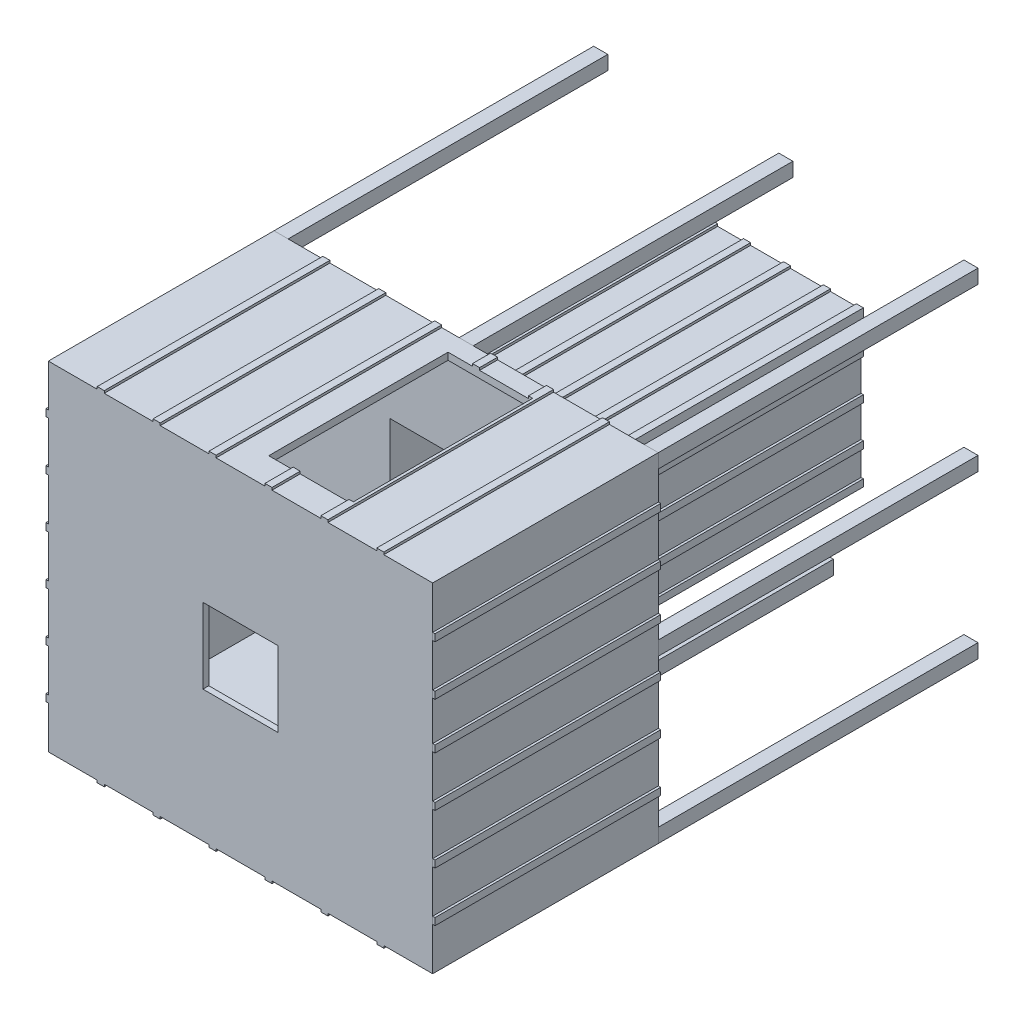
SolidWorks part; units mm, degrees
ref_plane "Front" through (0, 0, 0) normal (0, 0, 1) x (1, 0, 0)
ref_plane "Top" through (0, 0, 0) normal (0, 1, 0) x (1, 0, 0)
ref_plane "Right" through (0, 0, 0) normal (1, 0, 0) x (0, 0, -1)
sketch "Sketch1" plane through (0, 0, 0) normal (0, 0, 1) x (1, 0, 0)
  line L0 (-2076.45, 1828.8) -> (2076.45, -1828.8) construction
  line L1 (-2076.45, 1828.8) -> (2076.45, 1828.8)
  line L2 (-2076.45, 1828.8) -> (-2076.45, -1828.8)
  line L3 (-2076.45, -1828.8) -> (2076.45, -1828.8)
  line L4 (2076.45, 1828.8) -> (2076.45, -1828.8)
  line L5 (-2000.25, 1752.6) -> (-2000.25, -1752.6)
  line L6 (-2000.25, -1752.6) -> (2000.25, -1752.6)
  line L7 (2000.25, 1752.6) -> (2000.25, -1752.6)
  line L8 (-2000.25, 1752.6) -> (2000.25, 1752.6)
  point P4 (0, 0)
  dimension "D1" = 4152.9
  dimension "D2" = 3657.6
  dimension "D3" = 76.2
extrude "Base-Extrude" add sketch "Sketch1" along normal blind 2438.4
sketch "Sketch2" plane through (0, 0, 0) normal (0, 0, -1) x (-1, 0, 0)
  line L0 (-762, -762) -> (762, -762)
  line L1 (-762, 762) -> (-762, -762)
  line L2 (762, 762) -> (-762, 762)
  line L3 (762, -762) -> (762, 762)
  line L4 (2076.45, -1828.8) -> (2076.45, 1828.8)
  line L5 (2076.45, -1828.8) -> (2076.45, 1828.8)
  line L6 (2076.45, 1828.8) -> (-2076.45, 1828.8)
  line L7 (2076.45, 1828.8) -> (-2076.45, 1828.8)
  line L8 (-2076.45, 1828.8) -> (-2076.45, -1828.8)
  line L9 (-2076.45, 1828.8) -> (-2076.45, -1828.8)
  line L10 (-2076.45, -1828.8) -> (2076.45, -1828.8)
  line L11 (-2076.45, -1828.8) -> (2076.45, -1828.8)
  line L12 (-762, 762) -> (762, -762) construction
  dimension "D2" = 1524
  dimension "D3" = 1524
  dimension "D1" = 0
extrude "Boss-Extrude1" add sketch "Sketch2" against normal blind 63.5
sketch "Sketch3" plane through (0, 0, 2438.4) normal (0, 0, 1) x (1, 0, 0)
  line L0 (-406.4, 406.4) -> (406.4, -406.4) construction
  line L1 (-406.4, 406.4) -> (406.4, 406.4)
  line L2 (-406.4, 406.4) -> (-406.4, -406.4)
  line L3 (-406.4, -406.4) -> (406.4, -406.4)
  line L4 (-2076.45, 1828.8) -> (-2076.45, -1828.8)
  line L5 (-2076.45, 1828.8) -> (-2076.45, -1828.8)
  line L6 (-2076.45, -1828.8) -> (2076.45, -1828.8)
  line L7 (-2076.45, -1828.8) -> (2076.45, -1828.8)
  line L8 (2076.45, -1828.8) -> (2076.45, 1828.8)
  line L9 (2076.45, -1828.8) -> (2076.45, 1828.8)
  line L10 (2076.45, 1828.8) -> (-2076.45, 1828.8)
  line L11 (2076.45, 1828.8) -> (-2076.45, 1828.8)
  line L12 (406.4, 406.4) -> (406.4, -406.4)
  circle A1 centre (0, 0) radius 260
  circle A2 centre (0, 0) radius 260 construction
  dimension "D3" = 812.8
  dimension "D4" = 812.8
  dimension "D1" = 0
  dimension "D2" = 0
extrude "Boss-Extrude2" add sketch "Sketch3" against normal blind 63.5
sketch "Sketch4" plane through (0, 0, 0) normal (0, 0, -1) x (-1, 0, 0)
  line L0 (1924.05, 1828.8) -> (2076.45, 1828.8)
  line L1 (-2076.45, 1828.8) -> (2076.45, 1828.8) construction
  line L2 (2076.45, 1828.8) -> (2076.45, 1676.4)
  line L3 (2076.45, 1828.8) -> (2076.45, -1828.8) construction
  line L4 (2076.45, 1676.4) -> (1924.05, 1676.4)
  line L5 (1924.05, 1676.4) -> (1924.05, 1828.8)
  line L6 (0, 1875.0635) -> (0, -1962.1236) construction
  line L7 (-2052.0766, 0) -> (2208.6127, 0) construction
  line L8 (1924.05, -1676.4) -> (1924.05, -1828.8)
  line L9 (1924.05, -1828.8) -> (2076.45, -1828.8)
  line L10 (2076.45, -1828.8) -> (2076.45, -1676.4)
  line L11 (2076.45, -1676.4) -> (1924.05, -1676.4)
  line L12 (-2076.45, -1828.8) -> (-2076.45, -1676.4)
  line L13 (-1924.05, -1828.8) -> (-2076.45, -1828.8)
  line L14 (-1924.05, -1676.4) -> (-1924.05, -1828.8)
  line L15 (-2076.45, -1676.4) -> (-1924.05, -1676.4)
  line L16 (-2076.45, 1676.4) -> (-1924.05, 1676.4)
  line L17 (-1924.05, 1676.4) -> (-1924.05, 1828.8)
  line L18 (-2076.45, 1828.8) -> (-2076.45, 1676.4)
  line L19 (-1924.05, 1828.8) -> (-2076.45, 1828.8)
  line L20 (1928.8125, 1824.0375) -> (2071.6875, 1824.0375)
  line L21 (1928.8125, 1681.1625) -> (1928.8125, 1824.0375)
  line L22 (2071.6875, 1681.1625) -> (1928.8125, 1681.1625)
  line L23 (2071.6875, 1824.0375) -> (2071.6875, 1681.1625)
  line L24 (-2071.6875, 1824.0375) -> (-2071.6875, 1681.1625)
  line L25 (-1928.8125, 1824.0375) -> (-2071.6875, 1824.0375)
  line L26 (-1928.8125, 1681.1625) -> (-1928.8125, 1824.0375)
  line L27 (-2071.6875, 1681.1625) -> (-1928.8125, 1681.1625)
  line L28 (2071.6875, -1824.0375) -> (2071.6875, -1681.1625)
  line L29 (2071.6875, -1681.1625) -> (1928.8125, -1681.1625)
  line L30 (1928.8125, -1681.1625) -> (1928.8125, -1824.0375)
  line L31 (1928.8125, -1824.0375) -> (2071.6875, -1824.0375)
  line L32 (-1928.8125, -1681.1625) -> (-1928.8125, -1824.0375)
  line L33 (-2071.6875, -1681.1625) -> (-1928.8125, -1681.1625)
  line L34 (-2071.6875, -1824.0375) -> (-2071.6875, -1681.1625)
  line L35 (-1928.8125, -1824.0375) -> (-2071.6875, -1824.0375)
  line L36 (781.05, 2100.2481) -> (781.05, -2223.6723) construction
  line L37 (-2317.3549, -457.2) -> (2473.3024, -457.2) construction
  line L38 (709.6125, 1824.0375) -> (852.4875, 1824.0375) construction
  line L39 (704.85, 1828.8) -> (857.25, 1828.8) construction
  line L40 (704.85, 1828.8) -> (704.85, 1676.4) construction
  line L41 (704.85, 1676.4) -> (857.25, 1676.4) construction
  line L42 (857.25, 1828.8) -> (857.25, 1676.4) construction
  line L43 (852.4875, 1824.0375) -> (852.4875, 1681.1625) construction
  line L44 (709.6125, 1681.1625) -> (852.4875, 1681.1625) construction
  line L45 (709.6125, 1824.0375) -> (709.6125, 1681.1625) construction
  line L46 (-2076.45, -1828.8) -> (-2076.45, 1828.8) construction
  line L47 (-2076.45, -381) -> (-1924.05, -381) construction
  line L48 (-2076.45, -381) -> (-2076.45, -533.4) construction
  line L49 (-2076.45, -533.4) -> (-1924.05, -533.4) construction
  line L50 (-1924.05, -381) -> (-1924.05, -533.4) construction
  line L51 (-2071.6875, -385.7625) -> (-1928.8125, -385.7625) construction
  line L52 (-1928.8125, -385.7625) -> (-1928.8125, -528.6375) construction
  line L53 (-2071.6875, -528.6375) -> (-1928.8125, -528.6375) construction
  line L54 (-2071.6875, -385.7625) -> (-2071.6875, -528.6375) construction
  line L55 (2076.45, -1828.8) -> (-2076.45, -1828.8) construction
  line L56 (-76.2, -1828.8) -> (76.2, -1828.8) construction
  line L57 (-76.2, -1828.8) -> (-76.2, -1676.4) construction
  line L58 (-76.2, -1676.4) -> (76.2, -1676.4) construction
  line L59 (76.2, -1828.8) -> (76.2, -1676.4) construction
  line L60 (-71.4375, -1824.0375) -> (71.4375, -1824.0375) construction
  line L61 (71.4375, -1824.0375) -> (71.4375, -1681.1625) construction
  line L62 (-71.4375, -1681.1625) -> (71.4375, -1681.1625) construction
  line L63 (-71.4375, -1824.0375) -> (-71.4375, -1681.1625) construction
  line L64 (2071.6875, -71.4375) -> (1928.8125, -71.4375) construction
  line L65 (2076.45, -76.2) -> (1924.05, -76.2) construction
  line L66 (2076.45, -76.2) -> (2076.45, 76.2) construction
  line L67 (2076.45, 76.2) -> (1924.05, 76.2) construction
  line L68 (1924.05, -76.2) -> (1924.05, 76.2) construction
  line L69 (1928.8125, -71.4375) -> (1928.8125, 71.4375) construction
  line L70 (2071.6875, 71.4375) -> (1928.8125, 71.4375) construction
  line L71 (2071.6875, -71.4375) -> (2071.6875, 71.4375) construction
  line L72 (-71.4375, 1824.0375) -> (-71.4375, 1681.1625)
  line L73 (-71.4375, 1681.1625) -> (71.4375, 1681.1625)
  line L74 (71.4375, 1824.0375) -> (71.4375, 1681.1625)
  line L75 (-71.4375, 1824.0375) -> (71.4375, 1824.0375)
  line L76 (76.2, 1828.8) -> (76.2, 1676.4)
  line L77 (-76.2, 1676.4) -> (76.2, 1676.4)
  line L78 (-76.2, 1828.8) -> (-76.2, 1676.4)
  line L79 (-76.2, 1828.8) -> (76.2, 1828.8)
  line L80 (-3099.1062, -533.4) -> (3294.2058, -533.4) construction
  line L81 (-2076.45, 1676.4) -> (-2076.45, -533.4) construction
  line L82 (-1924.05, 1676.4) -> (-1924.05, -533.4) construction
  line L83 (-1928.8125, -528.6375) -> (-1928.8125, -385.7625) construction
  line L84 (-1924.05, -533.4) -> (-2076.45, -533.4) construction
  line L85 (-1924.05, -533.4) -> (-1924.05, -381) construction
  line L86 (-1924.05, -381) -> (-2076.45, -381) construction
  line L87 (-2076.45, -533.4) -> (-2076.45, -381) construction
  line L88 (-1928.8125, -385.7625) -> (-2071.6875, -385.7625) construction
  line L89 (-2071.6875, -528.6375) -> (-2071.6875, -385.7625) construction
  line L90 (-1928.8125, -528.6375) -> (-2071.6875, -528.6375) construction
  line L91 (-361.95, -2223.6723) -> (-361.95, 2276.0035) construction
  line L92 (-1924.05, -1676.4) -> (1320.7273, -1676.4) construction
  line L93 (-366.7125, -1681.1625) -> (-509.5875, -1681.1625)
  line L94 (-361.95, -1676.4) -> (-514.35, -1676.4)
  line L95 (-361.95, -1676.4) -> (-361.95, -1828.8)
  line L96 (-361.95, -1828.8) -> (-514.35, -1828.8)
  line L97 (-514.35, -1676.4) -> (-514.35, -1828.8)
  line L98 (-509.5875, -1681.1625) -> (-509.5875, -1824.0375)
  line L99 (-366.7125, -1824.0375) -> (-509.5875, -1824.0375)
  line L100 (-366.7125, -1681.1625) -> (-366.7125, -1824.0375)
  line L101 (-2071.6875, -71.4375) -> (-2071.6875, 71.4375)
  line L102 (-2071.6875, 71.4375) -> (-1928.8125, 71.4375)
  line L103 (-1928.8125, -71.4375) -> (-1928.8125, 71.4375)
  line L104 (-1924.05, -76.2) -> (-1924.05, 76.2)
  line L105 (-2076.45, 76.2) -> (-1924.05, 76.2)
  line L106 (-2076.45, -76.2) -> (-2076.45, 76.2)
  line L107 (-2076.45, -76.2) -> (-1924.05, -76.2)
  line L108 (-2071.6875, -71.4375) -> (-1928.8125, -71.4375)
  line L109 (1924.05, -381) -> (2076.45, -381)
  line L110 (1928.8125, -385.7625) -> (2071.6875, -385.7625)
  line L111 (2076.45, -533.4) -> (2076.45, -381)
  line L112 (2071.6875, -528.6375) -> (2071.6875, -385.7625)
  line L113 (1928.8125, -528.6375) -> (2071.6875, -528.6375)
  line L114 (1924.05, -533.4) -> (2076.45, -533.4)
  line L115 (1924.05, -533.4) -> (1924.05, -381)
  line L116 (1928.8125, -528.6375) -> (1928.8125, -385.7625)
  point P50 (781.05, 1828.8)
  point P61 (-2076.45, -457.2)
  point P72 (0, -1828.8)
  point P81 (2076.45, 0)
  dimension "D1" = 152.4
  dimension "D2" = 152.4
  dimension "D4" = 1295.4
  dimension "D5" = 2286
  dimension "D6" = 152.4
  dimension "D7" = 152.4
  dimension "D9" = 152.4
  dimension "D10" = 152.4
  dimension "D12" = 152.4
  dimension "D13" = 152.4
  dimension "D15" = 152.4
  dimension "D16" = 152.4
  dimension "D18" = 1295.4
  dimension "D19" = 152.4
  dimension "D21" = 2438.4
  dimension "D22" = 152.4
  dimension "D3" = 4.7625
  dimension "D8" = 4.7625
  dimension "D11" = 4.7625
  dimension "D14" = 4.7625
  dimension "D17" = 4.7625
  dimension "D20" = 4.7625
  dimension "D23" = 4.7625
extrude "Boss-Extrude3" add sketch "Sketch4" along normal blind 3454.4
sketch "Sketch9" plane through (0, 1828.8, 0) normal (0, 1, 0) x (-1, 0, 0)
  line L0 (1924.05, 0) -> (2076.45, 0)
  line L1 (2076.45, 2438.4) -> (2076.45, -3454.4) construction
  line L2 (-1924.05, 0) -> (-2076.45, 0)
  line L3 (-2076.45, 2438.4) -> (-2076.45, -3454.4) construction
  line L4 (76.2, 0) -> (-76.2, 0)
split line "Split Line4"
sketch "Sketch10" plane through (2076.45, 0, 0) normal (1, 0, 0) x (0, 0, -1)
  line L0 (0, -1676.4) -> (0, -1828.8)
  line L1 (-2438.4, -1828.8) -> (3454.4, -1828.8) construction
  line L2 (0, 76.2) -> (0, -76.2)
  line L3 (0, 1676.4) -> (0, 1828.8)
split line "Split Line5"
sketch "Sketch11" plane through (0, -1828.8, 0) normal (0, -1, 0) x (1, 0, 0)
  line L0 (514.35, 0) -> (361.95, 0)
  line L1 (-1924.05, 0) -> (-2076.45, 0)
  line L2 (-2076.45, 2438.4) -> (-2076.45, -3454.4) construction
  line L3 (1924.05, 0) -> (2076.45, 0)
split line "Split Line6"
sketch "Sketch12" plane through (-2076.45, 0, 0) normal (-1, 0, 0) x (0, 0, 1)
  line L0 (0, 1828.8) -> (0, 1676.4)
  line L1 (0, -381) -> (0, -533.4)
  line L2 (0, -1676.4) -> (0, -1828.8)
split line "Split Line7"
sketch "Sketch13" plane through (0, 1828.8, 0) normal (0, 1, 0) x (1, 0, 0)
  line L0 (1924.05, 0) -> (76.2, 0) construction
  line L1 (1548.4929, 0) -> (1472.2929, 0)
  line L2 (1548.4929, 0) -> (1548.4929, -2438.4)
  line L3 (1548.4929, -2438.4) -> (1472.2929, -2438.4)
  line L4 (1472.2929, 0) -> (1472.2929, -2438.4)
  line L5 (2076.45, -2438.4) -> (-2076.45, -2438.4) construction
  line L6 (-76.2, 0) -> (-1924.05, 0) construction
  line L7 (944.3357, 0) -> (868.1357, 0)
  line L8 (944.3357, 0) -> (944.3357, -2438.4)
  line L9 (944.3357, -2438.4) -> (868.1357, -2438.4)
  line L10 (868.1357, 0) -> (868.1357, -2438.4)
  line L11 (340.1786, 0) -> (263.9786, 0)
  line L12 (340.1786, 0) -> (340.1786, -2438.4)
  line L13 (340.1786, -2438.4) -> (263.9786, -2438.4)
  line L14 (263.9786, 0) -> (263.9786, -2438.4)
  line L15 (-263.9786, 0) -> (-340.1786, 0)
  line L16 (-263.9786, 0) -> (-263.9786, -2438.4)
  line L17 (-263.9786, -2438.4) -> (-340.1786, -2438.4)
  line L18 (-340.1786, 0) -> (-340.1786, -2438.4)
  line L19 (-868.1357, 0) -> (-944.3357, 0)
  line L20 (-868.1357, 0) -> (-868.1357, -2438.4)
  line L21 (-868.1357, -2438.4) -> (-944.3357, -2438.4)
  line L22 (-944.3357, 0) -> (-944.3357, -2438.4)
  line L23 (1548.4929, -2438.4) -> (2076.45, -2438.4)
  line L24 (-1472.2929, 0) -> (-1548.4929, 0)
  line L25 (-1472.2929, 0) -> (-1472.2929, -2438.4)
  line L26 (-1472.2929, -2438.4) -> (-1548.4929, -2438.4)
  line L27 (-1548.4929, 0) -> (-1548.4929, -2438.4)
  line L28 (-2076.45, -2438.4) -> (-2076.45, 0) construction
  line L32 (-2076.45, -2438.4) -> (-1548.4929, -2438.4)
  line L33 (-1472.2929, -2438.4) -> (-944.3357, -2438.4)
  line L34 (-868.1357, -2438.4) -> (-340.1786, -2438.4)
  line L35 (-263.9786, -2438.4) -> (263.9786, -2438.4)
  line L36 (263.9786, -2438.4) -> (254.571, -2429.2212)
  line L37 (340.1786, -2438.4) -> (868.1357, -2438.4)
  line L38 (944.3357, -2438.4) -> (1472.2929, -2438.4)
  line L39 (1548.4929, -2438.4) -> (2076.45, -2438.4)
  line M2 (-76.2, 0) -> (-1924.05, 0)
  line M5 (-2076.45, -2438.4) -> (2076.45, -2438.4)
  line M8 (1924.05, 0) -> (76.2, 0)
  dimension "D1" = 76.2
  dimension "D2" = 76.2
  dimension "D3" = 76.2
  dimension "D4" = 76.2
  dimension "D5" = 76.2
  dimension "D6" = 76.2
extrude "Boss-Extrude5" add sketch "Sketch13" along normal blind 25.4 contours L27 L25 M2 M5 | L22 L20 M2 M5 | L18 L16 M2 M5 | L14 L12 M8 M5 | L10 L8 M8 M5 | L4 L2 M8 M5
sketch "Sketch15" plane through (0, -1828.8, 0) normal (0, -1, 0) x (1, 0, 0)
  line L0 (1548.4929, 2438.4) -> (1472.2929, 2438.4)
  line L1 (1548.4929, 2438.4) -> (1548.4929, 0)
  line L2 (1548.4929, 0) -> (1472.2929, 0)
  line L3 (1472.2929, 2438.4) -> (1472.2929, 0)
  line L4 (944.3357, 2438.4) -> (868.1357, 2438.4)
  line L5 (944.3357, 2438.4) -> (944.3357, 0)
  line L6 (944.3357, 0) -> (868.1357, 0)
  line L7 (868.1357, 2438.4) -> (868.1357, 0)
  line L8 (340.1786, 2438.4) -> (263.9786, 2438.4)
  line L9 (340.1786, 2438.4) -> (340.1786, 0)
  line L10 (340.1786, 0) -> (263.9786, 0)
  line L11 (263.9786, 2438.4) -> (263.9786, 0)
  line L12 (-263.9786, 2438.4) -> (-340.1786, 2438.4)
  line L13 (-263.9786, 2438.4) -> (-263.9786, 0)
  line L14 (-263.9786, 0) -> (-340.1786, 0)
  line L15 (-340.1786, 2438.4) -> (-340.1786, 0)
  line L16 (-868.1357, 2438.4) -> (-944.3357, 2438.4)
  line L17 (-868.1357, 2438.4) -> (-868.1357, 0)
  line L18 (-868.1357, 0) -> (-944.3357, 0)
  line L19 (-944.3357, 2438.4) -> (-944.3357, 0)
  line L20 (1548.4929, 0) -> (2076.45, 0)
  line L21 (-1472.2929, 2438.4) -> (-1548.4929, 2438.4)
  line L22 (-1472.2929, 2438.4) -> (-1472.2929, 0)
  line L23 (-1472.2929, 0) -> (-1548.4929, 0)
  line L24 (-1548.4929, 2438.4) -> (-1548.4929, 0)
  line L25 (-2076.45, 0) -> (-1548.4929, 0)
  line L26 (-1472.2929, 0) -> (-944.3357, 0)
  line L27 (-868.1357, 0) -> (-340.1786, 0)
  line L28 (-263.9786, 0) -> (263.9786, 0)
  line L29 (-2076.45, 2438.4) -> (2076.45, 2438.4) construction
  line L30 (340.1786, 0) -> (868.1357, 0)
  line L31 (944.3357, 0) -> (1472.2929, 0)
  line L32 (1548.4929, 0) -> (2076.45, 0)
  line L33 (-2076.45, 2438.4) -> (-2076.45, 0) construction
  line M1 (514.35, 0) -> (1924.05, 0)
  line M4 (2076.45, 2438.4) -> (-2076.45, 2438.4)
  line M7 (-1924.05, 0) -> (361.95, 0)
  dimension "D1" = 76.2
  dimension "D2" = 76.2
  dimension "D3" = 76.2
  dimension "D4" = 76.2
  dimension "D5" = 76.2
  dimension "D6" = 76.2
extrude "Boss-Extrude6" add sketch "Sketch15" along normal blind 25.4 contours L24 L22 M4 M7 | L19 L17 M4 M7 | L15 L13 M4 M7 | L11 L9 M4 M7 | L7 L5 M4 M1 | L3 L1 M4 M1
sketch "Sketch16" plane through (2076.45, 0, 0) normal (1, 0, 0) x (0, 0, -1)
  line L0 (0, -1676.4) -> (0, -76.2) construction
  line L1 (0, -1366.3407) -> (-2438.4, -1366.3407)
  line L2 (0, -1366.3407) -> (0, -1290.1407)
  line L3 (0, -1290.1407) -> (-2438.4, -1290.1407)
  line L4 (-2438.4, -1366.3407) -> (-2438.4, -1290.1407)
  line L5 (-2438.4, -1828.8) -> (-2438.4, 1828.8) construction
  line L6 (0, -827.6815) -> (-2438.4, -827.6815)
  line L7 (0, -827.6815) -> (0, -751.4815)
  line L8 (0, -751.4815) -> (-2438.4, -751.4815)
  line L9 (-2438.4, -827.6815) -> (-2438.4, -751.4815)
  line L10 (0, -289.0222) -> (-2438.4, -289.0222)
  line L11 (0, -289.0222) -> (0, -212.8222)
  line L12 (0, -212.8222) -> (-2438.4, -212.8222)
  line L13 (-2438.4, -289.0222) -> (-2438.4, -212.8222)
  line L14 (0, 249.637) -> (-2438.4, 249.637)
  line L15 (0, 249.637) -> (0, 325.837)
  line L16 (0, 325.837) -> (-2438.4, 325.837)
  line L17 (-2438.4, 249.637) -> (-2438.4, 325.837)
  line L18 (0, 751.4815) -> (-2438.4, 751.4815)
  line L19 (0, 751.4815) -> (0, 827.6815)
  line L20 (0, 827.6815) -> (-2438.4, 827.6815)
  line L21 (-2438.4, 751.4815) -> (-2438.4, 827.6815)
  line L22 (0, 1290.1407) -> (-2438.4, 1290.1407)
  line L23 (0, 1290.1407) -> (0, 1366.3407)
  line L24 (0, 1366.3407) -> (-2438.4, 1366.3407)
  line L25 (-2438.4, 1290.1407) -> (-2438.4, 1366.3407)
  line L26 (0, 76.2) -> (0, 1676.4) construction
  line L27 (0, -1828.8) -> (0, -1366.3407)
  line L28 (0, -1290.1407) -> (0, -827.6815)
  line L29 (0, -751.4815) -> (0, -289.0222)
  line L30 (0, -212.8222) -> (0, 249.637)
  line L31 (0, 325.837) -> (0, 751.4815)
  line L32 (0, 827.6815) -> (0, 1290.1407)
  line L33 (0, 1366.3407) -> (0, 1828.8)
  line M1 (0, 76.2) -> (0, 1676.4)
  line M4 (-2438.4, 1828.8) -> (-2438.4, -1828.8)
  line M7 (0, -1676.4) -> (0, -76.2)
  dimension "D1" = 76.2
  dimension "D2" = 76.2
  dimension "D3" = 76.2
  dimension "D4" = 76.2
  dimension "D5" = 76.2
  dimension "D6" = 76.2
extrude "Boss-Extrude7" add sketch "Sketch16" along normal blind 25.4 separate body contours L3 L1 M7 M4 | L8 L6 M7 M4 | L12 L10 M7 M4 | L16 L14 M1 M4 | L20 L18 M1 M4 | L24 L22 M1 M4
sketch "Sketch19" plane through (-2076.45, 0, 0) normal (-1, 0, 0) x (0, 0, 1)
  line L0 (2438.4, -1371.6) -> (0, -1371.6)
  line L1 (2438.4, -1371.6) -> (2438.4, -1295.4)
  line L2 (2438.4, -1295.4) -> (0, -1295.4)
  line L3 (0, -1371.6) -> (0, -1295.4)
  line L4 (2438.4, -838.2) -> (0, -838.2)
  line L5 (2438.4, -838.2) -> (2438.4, -762)
  line L6 (2438.4, -762) -> (0, -762)
  line L7 (0, -838.2) -> (0, -762)
  line L8 (2438.4, -304.8) -> (0, -304.8)
  line L9 (2438.4, -304.8) -> (2438.4, -228.6)
  line L10 (2438.4, -228.6) -> (0, -228.6)
  line L11 (0, -304.8) -> (0, -228.6)
  line L12 (2438.4, 228.6) -> (0, 228.6)
  line L13 (2438.4, 228.6) -> (2438.4, 304.8)
  line L14 (2438.4, 304.8) -> (0, 304.8)
  line L15 (0, 228.6) -> (0, 304.8)
  line L16 (2438.4, 762) -> (0, 762)
  line L17 (2438.4, 762) -> (2438.4, 838.2)
  line L18 (2438.4, 838.2) -> (0, 838.2)
  line L19 (0, 762) -> (0, 838.2)
  line L20 (2438.4, 1295.4) -> (0, 1295.4)
  line L21 (2438.4, 1295.4) -> (2438.4, 1371.6)
  line L22 (2438.4, 1371.6) -> (0, 1371.6)
  line L23 (0, 1295.4) -> (0, 1371.6)
  line L24 (2438.4, -1828.8) -> (2438.4, -1371.6)
  line L25 (2438.4, -1295.4) -> (2438.4, -838.2)
  line L26 (2438.4, -762) -> (2438.4, -304.8)
  line L27 (2438.4, -228.6) -> (2438.4, 228.6)
  line L28 (2438.4, 304.8) -> (2438.4, 762)
  line L29 (2438.4, 838.2) -> (2438.4, 1295.4)
  line L30 (2438.4, 1371.6) -> (2438.4, 1828.8)
  line L31 (0, 1676.4) -> (0, -381) construction
  line L32 (0, -533.4) -> (0, -1676.4) construction
  line M1 (0, -533.4) -> (0, -1676.4)
  line M4 (2438.4, -1828.8) -> (2438.4, 1828.8)
  line M7 (0, 1676.4) -> (0, -381)
  dimension "D1" = 76.2
  dimension "D2" = 76.2
  dimension "D3" = 76.2
  dimension "D4" = 76.2
  dimension "D5" = 76.2
  dimension "D6" = 76.2
extrude "Boss-Extrude8" add sketch "Sketch19" along normal blind 25.4 contours L22 L20 M4 M7 | L18 L16 M4 M7 | L14 L12 M4 M7 | L10 L8 M4 M7 | L6 L4 M4 M1 | L2 L0 M4 M1
sketch "Sketch22" plane through (0, 0, 0) normal (0, 0, -1) x (-1, 0, 0)
  line L1 (-762, 762) -> (762, 762)
  line L2 (-762, 762) -> (-762, -762)
  line L3 (-762, -762) -> (762, -762)
  line L4 (762, 762) -> (762, -762)
  line L5 (-762, 762) -> (762, -762) construction
  line L6 (-762, -762) -> (762, 762) construction
  line L7 (-812.8, 812.8) -> (812.8, 812.8)
  line L8 (-812.8, 812.8) -> (-812.8, -812.8)
  line L9 (-812.8, -812.8) -> (812.8, -812.8)
  line L10 (812.8, 812.8) -> (812.8, -812.8)
  line L11 (-812.8, 812.8) -> (812.8, -812.8) construction
  line L12 (-812.8, -812.8) -> (812.8, 812.8) construction
  point P0 (0, 0)
  point P7 (0, 0)
  dimension "D1" = 50.8
extrude "Boss-Extrude9" add sketch "Sketch22" along normal up to vertex (3454.4 mm away)
sketch "Sketch24" plane through (0, -812.8, 0) normal (0, -1, 0) x (1, 0, 0)
  line L0 (812.8, -3454.4) -> (-812.8, -3454.4) construction
  line L1 (-463.55, -3454.4) -> (-387.35, -3454.4)
  line L2 (-463.55, -3454.4) -> (-463.55, 0)
  line L3 (-463.55, 0) -> (-387.35, 0)
  line L4 (-387.35, -3454.4) -> (-387.35, 0)
  line L5 (812.8, 0) -> (-812.8, 0) construction
  line L6 (-38.1, -3454.4) -> (38.1, -3454.4)
  line L7 (-38.1, -3454.4) -> (-38.1, 0)
  line L8 (-38.1, 0) -> (38.1, 0)
  line L9 (38.1, -3454.4) -> (38.1, 0)
  line L10 (387.35, -3454.4) -> (463.55, -3454.4)
  line L11 (387.35, -3454.4) -> (387.35, 0)
  line L12 (387.35, 0) -> (463.55, 0)
  line L13 (463.55, -3454.4) -> (463.55, 0)
  line L15 (-812.8, -3454.4) -> (-463.55, -3454.4)
  line L16 (-387.35, -3454.4) -> (-38.1, -3454.4)
  line L17 (38.1, -3454.4) -> (387.35, -3454.4)
  line L18 (463.55, -3454.4) -> (812.8, -3454.4)
  line L19 (-812.8, -3454.4) -> (-736.6, -3454.4)
  line L20 (-812.8, -3454.4) -> (-812.8, 0)
  line L21 (-812.8, 0) -> (-736.6, 0)
  line L22 (-736.6, -3454.4) -> (-736.6, 0)
  line L23 (812.8, 0) -> (736.6, 0)
  line L24 (812.8, 0) -> (812.8, -3454.4)
  line L25 (812.8, -3454.4) -> (736.6, -3454.4)
  line L26 (736.6, 0) -> (736.6, -3454.4)
  line M1 (812.8, 0) -> (-812.8, 0)
  line M2 (-812.8, 0) -> (-812.8, -3454.4)
  line M3 (-812.8, -3454.4) -> (812.8, -3454.4)
  line M4 (812.8, -3454.4) -> (812.8, 0)
  dimension "D1" = 76.2
  dimension "D2" = 76.2
  dimension "D3" = 76.2
  dimension "D4" = 76.2
  dimension "D5" = 76.2
extrude "Boss-Extrude10" add sketch "Sketch24" along normal blind 25.4 contours L22 M3 M1 M2 | L4 L2 M3 M1 | L9 L7 M3 M1 | L13 L11 M3 M1 | L26 L18 M1 M4
sketch "Sketch27" plane through (812.8, 0, 0) normal (1, 0, 0) x (0, 0, -1)
  line L0 (3454.4, 812.8) -> (3454.4, -838.2) construction
  line L1 (3454.4, -482.6) -> (0, -482.6)
  line L2 (3454.4, -482.6) -> (3454.4, -406.4)
  line L3 (3454.4, -406.4) -> (0, -406.4)
  line L4 (0, -482.6) -> (0, -406.4)
  line L5 (0, 812.8) -> (0, -838.2) construction
  line L6 (3454.4, -838.2) -> (3454.4, -482.6)
  line L7 (0, -50.8) -> (3454.4, -50.8)
  line L8 (0, -50.8) -> (0, 25.4)
  line L9 (0, 25.4) -> (3454.4, 25.4)
  line L10 (3454.4, -50.8) -> (3454.4, 25.4)
  line L11 (0, 381) -> (3454.4, 381)
  line L12 (0, 381) -> (0, 457.2)
  line L13 (0, 457.2) -> (3454.4, 457.2)
  line L14 (3454.4, 381) -> (3454.4, 457.2)
  line L15 (3454.4, -406.4) -> (3454.4, -50.8)
  line L16 (3454.4, 25.4) -> (3454.4, 381)
  line L17 (3454.4, 457.2) -> (3454.4, 812.8)
  line L19 (3454.4, -838.2) -> (0, -838.2)
  line L20 (3454.4, -838.2) -> (3454.4, -762)
  line L21 (3454.4, -762) -> (0, -762)
  line L22 (0, -838.2) -> (0, -762)
  line L23 (3454.4, 812.8) -> (0, 812.8)
  line L24 (3454.4, 812.8) -> (3454.4, 736.6)
  line L25 (3454.4, 736.6) -> (0, 736.6)
  line L26 (0, 812.8) -> (0, 736.6)
  line M1 (0, 812.8) -> (0, -838.2)
  line M2 (0, -838.2) -> (3454.4, -838.2)
  line M3 (3454.4, -838.2) -> (3454.4, 812.8)
  line M4 (3454.4, 812.8) -> (0, 812.8)
  dimension "D1" = 76.2
  dimension "D2" = 76.2
  dimension "D3" = 76.2
  dimension "D4" = 76.2
  dimension "D5" = 76.2
extrude "Boss-Extrude11" add sketch "Sketch27" along normal blind 25.4 contours L21 M3 M1 M2 | L3 L1 M3 M1 | L9 L7 M1 M3 | L13 L11 M1 M3 | L25 L17 M4 M1
sketch "Sketch28" plane through (0, 812.8, 0) normal (0, 1, 0) x (1, 0, 0)
  line L0 (-812.8, 3454.4) -> (838.2, 3454.4) construction
  line L1 (482.6, 3454.4) -> (406.4, 3454.4)
  line L2 (482.6, 3454.4) -> (482.6, 0)
  line L3 (482.6, 0) -> (406.4, 0)
  line L4 (406.4, 3454.4) -> (406.4, 0)
  line L5 (-812.8, 0) -> (838.2, 0) construction
  line L6 (482.6, 3454.4) -> (838.2, 3454.4)
  line L7 (50.8, 0) -> (-25.4, 0)
  line L8 (50.8, 0) -> (50.8, 3454.4)
  line L9 (50.8, 3454.4) -> (-25.4, 3454.4)
  line L10 (-25.4, 0) -> (-25.4, 3454.4)
  line L11 (-381, 3454.4) -> (-457.2, 3454.4)
  line L12 (-381, 3454.4) -> (-381, 0)
  line L13 (-381, 0) -> (-457.2, 0)
  line L14 (-457.2, 3454.4) -> (-457.2, 0)
  line L15 (406.4, 3454.4) -> (50.8, 3454.4)
  line L16 (-25.4, 3454.4) -> (-381, 3454.4)
  line L17 (-457.2, 3454.4) -> (-812.8, 3454.4)
  line L19 (838.2, 3454.4) -> (762, 3454.4)
  line L20 (838.2, 3454.4) -> (838.2, 0)
  line L21 (838.2, 0) -> (762, 0)
  line L22 (762, 3454.4) -> (762, 0)
  line L23 (-812.8, 0) -> (-736.6, 0)
  line L24 (-812.8, 0) -> (-812.8, 3454.4)
  line L25 (-812.8, 3454.4) -> (-736.6, 3454.4)
  line L26 (-736.6, 0) -> (-736.6, 3454.4)
  line M1 (-812.8, 0) -> (838.2, 0)
  line M2 (838.2, 0) -> (838.2, 3454.4)
  line M3 (838.2, 3454.4) -> (-812.8, 3454.4)
  line M4 (-812.8, 3454.4) -> (-812.8, 0)
  dimension "D1" = 76.2
  dimension "D2" = 76.2
  dimension "D3" = 76.2
  dimension "D4" = 76.2
  dimension "D5" = 76.2
extrude "Boss-Extrude12" add sketch "Sketch28" along normal blind 25.4 contours L22 M3 M1 M2 | L4 L2 M3 M1 | L10 L8 M1 M3 | L14 L12 M3 M1 | L26 L17 M1 M4
sketch "Sketch29" plane through (-812.8, 0, 0) normal (-1, 0, 0) x (0, 0, 1)
  line L0 (0, -838.2) -> (0, 838.2) construction
  line L1 (0, 476.25) -> (-3454.4, 476.25)
  line L2 (0, 476.25) -> (0, 400.05)
  line L3 (0, 400.05) -> (-3454.4, 400.05)
  line L4 (-3454.4, 476.25) -> (-3454.4, 400.05)
  line L5 (-3454.4, -838.2) -> (-3454.4, 838.2) construction
  line L6 (-3454.4, 838.2) -> (-3454.4, 476.25)
  line L7 (0, 38.1) -> (-3454.4, 38.1)
  line L8 (0, 38.1) -> (0, -38.1)
  line L9 (0, -38.1) -> (-3454.4, -38.1)
  line L10 (-3454.4, 38.1) -> (-3454.4, -38.1)
  line L11 (0, -400.05) -> (-3454.4, -400.05)
  line L12 (0, -400.05) -> (0, -476.25)
  line L13 (0, -476.25) -> (-3454.4, -476.25)
  line L14 (-3454.4, -400.05) -> (-3454.4, -476.25)
  line L15 (-3454.4, 400.05) -> (-3454.4, 38.1)
  line L16 (-3454.4, -38.1) -> (-3454.4, -400.05)
  line L17 (-3454.4, -476.25) -> (-3454.4, -838.2)
  line L19 (0, 838.2) -> (-3454.4, 838.2)
  line L20 (0, 838.2) -> (0, 762)
  line L21 (0, 762) -> (-3454.4, 762)
  line L22 (-3454.4, 838.2) -> (-3454.4, 762)
  line L23 (-3454.4, -838.2) -> (0, -838.2)
  line L24 (-3454.4, -838.2) -> (-3454.4, -762)
  line L25 (-3454.4, -762) -> (0, -762)
  line L26 (0, -838.2) -> (0, -762)
  line M1 (0, -838.2) -> (0, 838.2)
  line M2 (0, 838.2) -> (-3454.4, 838.2)
  line M3 (-3454.4, 838.2) -> (-3454.4, -838.2)
  line M4 (-3454.4, -838.2) -> (0, -838.2)
  dimension "D1" = 76.2
  dimension "D2" = 76.2
  dimension "D3" = 76.2
  dimension "D4" = 76.2
  dimension "D5" = 76.2
extrude "Boss-Extrude13" add sketch "Sketch29" along normal blind 25.4 contours L21 M1 M2 M3 | L3 L1 M1 M3 | L9 L7 M1 M3 | L13 L11 M1 M3 | L25 L17 M4 M1
sketch "Sketch31" plane through (-812.8, 0, 0) normal (-1, 0, 0) x (0, 0, 1)
  line L0 (-3454.4, 38.1) -> (-3454.4, 400.05) construction
  line L1 (-3454.4, 497.2184) -> (-1473.2, 497.2184)
  line L2 (-3454.4, 497.2184) -> (-3454.4, -493.3816)
  line L3 (-3454.4, -493.3816) -> (-1473.2, -493.3816)
  line L4 (-1473.2, 497.2184) -> (-1473.2, -493.3816)
  line L5 (-3454.4, 476.25) -> (-3454.4, 762) construction
  dimension "D1" = 990.6
  dimension "D2" = 1981.2
extrude "Cut-Extrude5" cut sketch "Sketch31" against normal blind 320.04 and the other way blind 293.37
sketch "Sketch33" plane through (0, 1828.8, 0) normal (0, 1, 0) x (1, 0, 0)
  line L7 (868.1357, 0) -> (340.1786, 0) construction
  line L8 (914.4, 0) -> (-914.4, 0)
  line L9 (914.4, 0) -> (914.4, -2133.6)
  line L10 (914.4, -2133.6) -> (-914.4, -2133.6)
  line L11 (-914.4, 0) -> (-914.4, -2133.6)
  line L12 (914.4, 0) -> (2076.45, 0)
  line L13 (-914.4, 0) -> (-2076.45, 0)
  line L14 (914.4, -76.2) -> (-914.4, -76.2)
  line M1 (263.9786, -2438.4) -> (263.9786, 0)
  line M5 (-263.9786, 0) -> (-263.9786, -2438.4)
  dimension "D4" = 1828.8
  dimension "D5" = 2133.6
  dimension "D6" = 76.2
extrude "Cut-Extrude6" cut sketch "Sketch33" against normal blind 655.574 and the other way blind 320.04 contours L9 L14 L10 M1 | L14 L10 M1 M5 | L14 L11 L10 M5
sketch "Sketch34" plane through (0, 0, 76.2) normal (0, 0, 1) x (1, 0, 0)
  line L16 (914.4, 1752.6) -> (914.4, 1854.2)
  line L17 (914.4, 1854.2) -> (868.1357, 1854.2)
  line L18 (868.1357, 1854.2) -> (868.1357, 1828.8)
  line L19 (868.1357, 1828.8) -> (340.1786, 1828.8)
  line L20 (340.1786, 1828.8) -> (340.1786, 1854.2)
  line L21 (340.1786, 1854.2) -> (263.9786, 1854.2)
  line L22 (263.9786, 1854.2) -> (263.9786, 1828.8)
  line L23 (263.9786, 1828.8) -> (-263.9786, 1828.8)
  line L24 (-263.9786, 1828.8) -> (-263.9786, 1854.2)
  line L25 (-263.9786, 1854.2) -> (-340.1786, 1854.2)
  line L26 (-340.1786, 1854.2) -> (-340.1786, 1828.8)
  line L27 (-340.1786, 1828.8) -> (-868.1357, 1828.8)
  line L28 (-868.1357, 1828.8) -> (-868.1357, 1854.2)
  line L29 (-868.1357, 1854.2) -> (-914.4, 1854.2)
  line L30 (-914.4, 1854.2) -> (-914.4, 1752.6)
  line L31 (-914.4, 1752.6) -> (914.4, 1752.6)
  line L32 (914.4, 1752.6) -> (914.4, 1854.2)
  line L33 (914.4, 1854.2) -> (868.1357, 1854.2)
  line L34 (868.1357, 1854.2) -> (868.1357, 1828.8)
  line L35 (868.1357, 1828.8) -> (340.1786, 1828.8)
  line L36 (340.1786, 1828.8) -> (340.1786, 1854.2)
  line L37 (340.1786, 1854.2) -> (263.9786, 1854.2)
  line L38 (263.9786, 1854.2) -> (263.9786, 1828.8)
  line L39 (263.9786, 1828.8) -> (-263.9786, 1828.8)
  line L40 (-263.9786, 1828.8) -> (-263.9786, 1854.2)
  line L41 (-263.9786, 1854.2) -> (-340.1786, 1854.2)
  line L42 (-340.1786, 1854.2) -> (-340.1786, 1828.8)
  line L43 (-340.1786, 1828.8) -> (-868.1357, 1828.8)
  line L44 (-868.1357, 1828.8) -> (-868.1357, 1854.2)
  line L45 (-868.1357, 1854.2) -> (-914.4, 1854.2)
  line L46 (-914.4, 1854.2) -> (-914.4, 1752.6)
  line L47 (-914.4, 1752.6) -> (914.4, 1752.6)
  dimension "D1" = 0
extrude "Boss-Extrude15" add sketch "Sketch34" along normal blind 119.38
sketch "Sketch35" plane through (0, 0, 195.58) normal (0, 0, 1) x (1, 0, 0)
  line L0 (0, 1828.8) -> (0, 1752.6)
  line L16 (-914.4, 1752.6) -> (914.4, 1752.6)
  line L17 (914.4, 1752.6) -> (914.4, 1854.2)
  line L18 (914.4, 1854.2) -> (868.1357, 1854.2)
  line L19 (868.1357, 1854.2) -> (868.1357, 1828.8)
  line L20 (868.1357, 1828.8) -> (340.1786, 1828.8)
  line L21 (340.1786, 1828.8) -> (340.1786, 1854.2)
  line L22 (340.1786, 1854.2) -> (263.9786, 1854.2)
  line L23 (263.9786, 1854.2) -> (263.9786, 1828.8)
  line L24 (263.9786, 1828.8) -> (-263.9786, 1828.8)
  line L25 (-263.9786, 1828.8) -> (-263.9786, 1854.2)
  line L26 (-263.9786, 1854.2) -> (-340.1786, 1854.2)
  line L27 (-340.1786, 1854.2) -> (-340.1786, 1828.8)
  line L28 (-340.1786, 1828.8) -> (-868.1357, 1828.8)
  line L29 (-868.1357, 1828.8) -> (-868.1357, 1854.2)
  line L30 (-868.1357, 1854.2) -> (-914.4, 1854.2)
  line L31 (-914.4, 1854.2) -> (-914.4, 1752.6)
  line L32 (-914.4, 1752.6) -> (0, 1752.6)
  line L40 (0, 1828.8) -> (-263.9786, 1828.8)
  line L41 (-263.9786, 1828.8) -> (-263.9786, 1854.2)
  line L42 (-263.9786, 1854.2) -> (-340.1786, 1854.2)
  line L43 (-340.1786, 1854.2) -> (-340.1786, 1828.8)
  line L44 (-340.1786, 1828.8) -> (-868.1357, 1828.8)
  line L45 (-868.1357, 1828.8) -> (-868.1357, 1854.2)
  line L46 (-868.1357, 1854.2) -> (-914.4, 1854.2)
  line L47 (-914.4, 1854.2) -> (-914.4, 1752.6)
  dimension "D1" = 0
extrude "Boss-Extrude16" add sketch "Sketch35" along normal up to next
